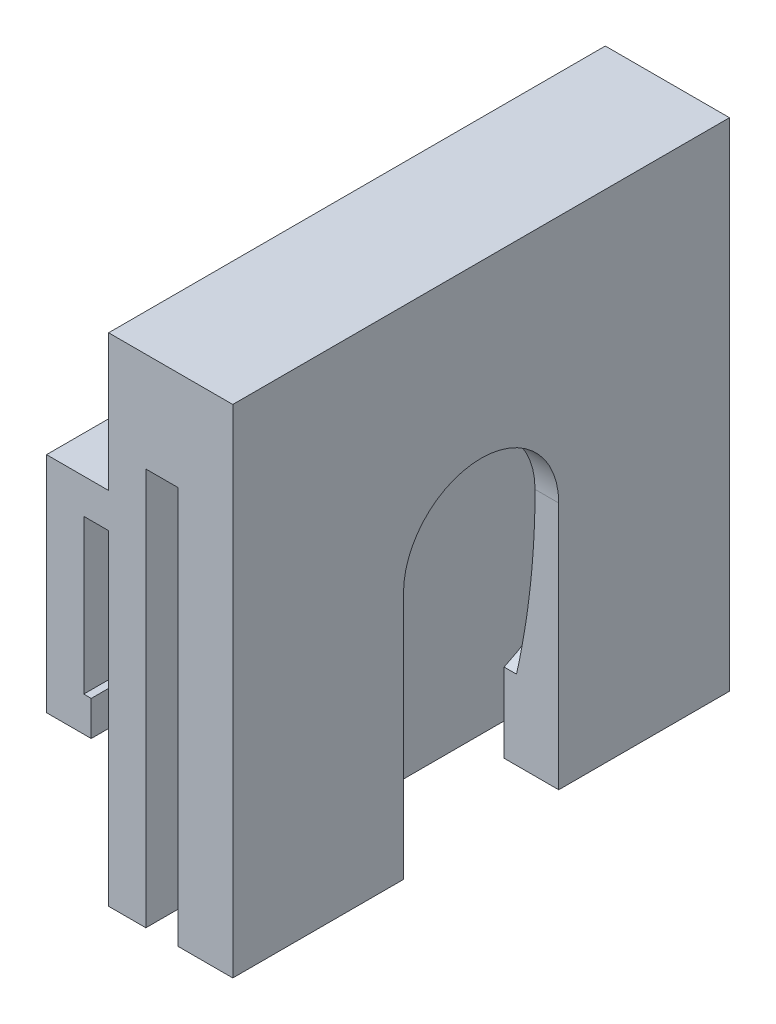
SolidWorks part; units mm, degrees
ref_plane "Plan de face" through (0, 0, 0) normal (0, 0, 1) x (1, 0, 0)
ref_plane "Plan de dessus" through (0, 0, 0) normal (0, 1, 0) x (1, 0, 0)
ref_plane "Plan de droite" through (0, 0, 0) normal (1, 0, 0) x (0, 0, -1)
sketch "Sketch1" plane through (0, 0, 0) normal (0, 0, 1) x (1, 0, 0)
  line L1 (2, 4.5) -> (-2, 4.5)
  line L2 (2, 4.5) -> (2, -4.5)
  line L3 (2, -4.5) -> (-2, -4.5)
  line L4 (-2, 4.5) -> (-2, -4.5)
  line L5 (2, 4.5) -> (-2, -4.5) construction
  line L6 (2, -4.5) -> (-2, 4.5) construction
  point P0 (0, 0)
  dimension "D1" = 9
  dimension "D2" = 4
extrude "Boss-Extrude1" add sketch "Sketch1" along normal blind 20
sketch "Sketch2" plane through (0, 0, 0) normal (0, 0, -1) x (-1, 0, 0)
  line L1 (0.5, 3) -> (-0.5, 3)
  line L2 (0.5, 3) -> (0.5, -3)
  line L3 (0.5, -3) -> (-0.5, -3)
  line L4 (-0.5, 3) -> (-0.5, -3)
  line L5 (0.5, 3) -> (-0.5, -3) construction
  line L6 (0.5, -3) -> (-0.5, 3) construction
  point P0 (0, 0)
  dimension "D1" = 1
  dimension "D2" = 6
extrude "Cut-Extrude1" cut sketch "Sketch2" against normal through all
sketch "Sketch4" plane through (2, 0, 0) normal (1, 0, 0) x (0, 0, -1)
  line L0 (-20, -4.5) -> (-20, 4.5) construction
  line L1 (-20, 10) -> (0, 10)
  line L2 (-20, 10) -> (-20, -10)
  line L3 (-20, -10) -> (0, -10)
  line L4 (0, 10) -> (0, -10)
  line L5 (0, -4.5) -> (0, 4.5) construction
  line L6 (-20, 10) -> (0, 4.5) construction
  line L7 (0, -4.5) -> (-20, -10) construction
extrude "Boss-Extrude2" add sketch "Sketch4" against normal up to surface (1.5 mm away) up to face at (0.5, 0, 10)
ref_plane "Plane1" through (2, 0, 0) normal (1, 0, 0) x (0, 0, -1)
ref_plane "Plane2" through (0, 0, 10) normal (0, 0, -1) x (-1, 0, 0)
ref_plane "Plane3" through (0, 0, 0) normal (0, 1, 0) x (1, 0, 0)
ref_axis "Axis1" through (88.99, 0, 10) along (-1, 0, 0)
sketch "Sketch5" plane through (2, 0, 0) normal (1, 0, 0) x (0, 0, -1)
  line L4 (0, -10) -> (0, 10)
  line L5 (0, -10) -> (0, 10)
  line L6 (0, 10) -> (-20, 10)
  line L7 (0, 10) -> (-20, 10)
  line L8 (-20, 10) -> (-20, -10)
  line L9 (-20, 10) -> (-20, -10)
  line L10 (-20, -10) -> (0, -10)
  line L11 (-20, -10) -> (0, -10)
  dimension "D1" = 0
extrude "Boss-Extrude3" add sketch "Sketch5" along normal blind 3.5
sketch "Sketch6" plane through (0, 0, 10) normal (0, 0, -1) x (-1, 0, 0)
  line L0 (-2, 7.5) -> (-2, 0)
  line L1 (-2, 0.825) -> (-2, -0.825) construction
  line L2 (-2, 7.5) -> (-3.8, 7.5)
  line L3 (-3.8, 7.5) -> (-3.8, 0) construction
  line L4 (55, 0) -> (-55, 0) construction
  line L5 (-5.5, 10) -> (-5.5, -10) construction
  line L6 (-5.5, 10) -> (-5.5, -10) construction
  line L7 (-5.5, 10) -> (-3.8, 7.5) construction
  line L9 (-2, 0) -> (-4.7003, 0)
  arc A0 (-3.8, 7.5) -> (-4.7003, 0) centre (26.99, 0) ccw
  dimension "D3" = 30.79
  dimension "D1" = 1.8
  dimension "D2" = 7.5
revolve "Cut-Revolve2" cut sketch "Sketch6" angle 360 about axis through (88.99, 0, 10) along (-1, 0, 0)
sketch "Sketch7" plane through (0, -10, 0) normal (0, -1, 0) x (1, 0, 0)
  line L0 (0.5, 20) -> (5.5, 20) construction
  line L1 (2, 20) -> (3.8, 20)
  line L2 (2, 20) -> (2, 0)
  line L3 (2, 0) -> (3.8, 0)
  line L4 (3.8, 20) -> (3.8, 0)
  line L5 (0.5, 0) -> (5.5, 0) construction
  line L6 (2, 2.5) -> (2, 17.5) construction
  line L7 (3.8, 2.5) -> (3.8, 17.5) construction
extrude "Cut-Extrude5" cut sketch "Sketch7" against normal blind 16
sketch "Sketch8" plane through (5.5, 0, 0) normal (1, 0, 0) x (0, 0, -1)
  line L0 (-10, 0) -> (-10, -10) construction
  line L1 (-6.875, 0) -> (-6.875, -10)
  line L2 (-13.125, 0) -> (-13.125, -10)
  line L3 (-10, -0.825) -> (-10, 0.825) construction
  line L4 (55, 0) -> (-55, 0) construction
  line L5 (-20, -10) -> (0, -10) construction
  arc A0 (-6.875, 0) -> (-13.125, 0) centre (-10, 0) ccw
  arc A1 (-13.125, -10) -> (-6.875, -10) centre (-10, -10) ccw
  point P2 (-10, -5)
  dimension "D1" = 6.25
extrude "Cut-Extrude6" cut sketch "Sketch8" against normal up to surface (1.7 mm away)
sketch "Sketch9" plane through (3.8, 0, 0) normal (-1, 0, 0) x (0, 0, 1)
  line L0 (13.125, -6.8179) -> (13.125, -10) construction
  line L1 (13.125, -10) -> (20, -10) construction
  line L2 (20, -10) -> (20, 6) construction
  line L3 (20, 6) -> (14.5, 6) construction
  line L4 (0, -10) -> (6.875, -10) construction
  line L5 (6.875, -10) -> (6.875, -6.8179) construction
  line L6 (5.5, 6) -> (0, 6) construction
  line L7 (0, 6) -> (0, -10) construction
  line L8 (13.125, -6.8179) -> (13.125, -10)
  line L9 (13.125, -10) -> (20, -10)
  line L10 (20, -10) -> (20, 6)
  line L11 (20, 6) -> (14.5, 6)
  line L12 (0, -10) -> (6.875, -10)
  line L13 (6.875, -10) -> (6.875, -6.8179)
  line L14 (5.5, 6) -> (0, 6)
  line L15 (0, 6) -> (0, -10)
  arc A0 (13.125, -6.8179) -> (14.5, 6) centre (10, 0) ccw construction
  arc A1 (5.5, 6) -> (6.875, -6.8179) centre (10, 0) ccw construction
  arc A2 (13.125, -6.8179) -> (14.5, 6) centre (10, 0) ccw
  arc A3 (5.5, 6) -> (6.875, -6.8179) centre (10, 0) ccw
extrude "Boss-Extrude4" add sketch "Sketch9" along normal blind 0.5
sketch "Sketch10" plane through (0, 0, 20) normal (0, 0, 1) x (1, 0, 0)
  line L0 (0.5, -3) -> (-0.5, -3) construction
  line L1 (0.5, -4.5) -> (-0.2, -4.5)
  line L2 (0.5, -4.5) -> (0.5, -3)
  line L3 (0.5, -3) -> (-0.2, -3)
  line L4 (-0.2, -4.5) -> (-0.2, -3)
  line L5 (-0.5, -3) -> (-0.5, 3) construction
  dimension "D1" = 0.3
extrude "Cut-Extrude7" cut sketch "Sketch10" against normal through all
sketch "Sketch11" plane through (0, 0, 20) normal (0, 0, 1) x (1, 0, 0)
  line L0 (-0.5, -3) -> (-0.5, 3) construction
  line L1 (-0.5, -3.1) -> (0.5, -3.1)
  line L2 (-0.5, -3.1) -> (-0.5, 3.1)
  line L3 (-0.5, 3.1) -> (0.5, 3.1)
  line L4 (0.5, -3.1) -> (0.5, 3.1)
  line L5 (0.5, 3) -> (0.5, -10) construction
  line L6 (-2, -4.5) -> (-0.5, -3.1) construction
  line L7 (-0.5, 3.1) -> (-2, 4.5) construction
  line L8 (-0.5, 3) -> (0.5, 3) construction
  dimension "D1" = 0.1
extrude "Cut-Extrude8" cut sketch "Sketch11" against normal through all
